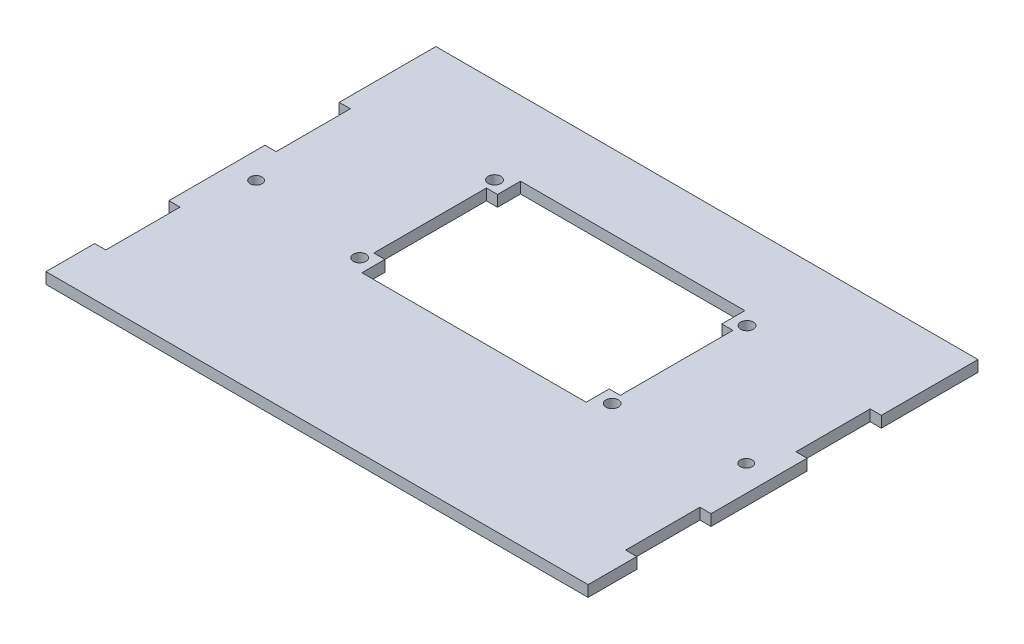
SolidWorks part; units mm, degrees
ref_plane "Front Plane" through (0, 0, 0) normal (0, 0, 1) x (1, 0, 0)
ref_plane "Top Plane" through (0, 0, 0) normal (0, 1, 0) x (1, 0, 0)
ref_plane "Right Plane" through (0, 0, 0) normal (1, 0, 0) x (0, 0, -1)
other "Configuration Table"
sketch "Sketch1" plane through (0, 0, 0) normal (0, 1, 0) x (1, 0, 0)
  line L1 (73, -52.5) -> (-73, -52.5)
  line L2 (73, -52.5) -> (73, 52.5)
  line L3 (73, 52.5) -> (-73, 52.5)
  line L4 (-73, -52.5) -> (-73, 52.5)
  line L5 (73, -52.5) -> (-73, 52.5) construction
  line L6 (73, 52.5) -> (-73, -52.5) construction
  point P0 (0, 0)
  dimension "D1" = 146
  dimension "D2" = 105
extrude "Boss-Extrude1" add sketch "Sketch1" along normal blind 3
sketch "Sketch2" plane through (0, 3, 0) normal (0, 1, 0) x (1, 0, 0)
  line L9 (73, -52.5) -> (73, 52.5) construction
  line L14 (-70, 26.47) -> (-70, 6.47)
  line L42 (-70, 26.47) -> (-73, 26.47)
  line L43 (-73, 52.5) -> (-73, -52.5) construction
  line L44 (-73, 26.47) -> (-73, 6.47)
  line L45 (-73, 6.47) -> (-70, 6.47)
  line L46 (70, 6.47) -> (70, 26.47)
  line L47 (70, 26.47) -> (73, 26.47)
  line L48 (73, 26.47) -> (73, 6.47)
  line L49 (73, 6.47) -> (70, 6.47)
  line L54 (-70, -39.4) -> (-70, -19.4)
  line L55 (-70, -19.4) -> (-73, -19.4)
  line L56 (-73, -19.4) -> (-73, -39.4)
  line L57 (-73, -39.4) -> (-70, -39.4)
  line L67 (70, -39.4) -> (70, -19.4)
  line L68 (70, -19.4) -> (73, -19.4)
  line L69 (73, -19.4) -> (73, -39.4)
  line L70 (73, -39.4) -> (70, -39.4)
  dimension "D2" = 13.1
  dimension "D9" = 20
  dimension "D11" = 3
  dimension "D12" = 25.87
  dimension "D13" = 20
extrude "Cut-Extrude1" cut sketch "Sketch2" against normal blind 10
sketch "Sketch3" plane through (0, 0, 0) normal (0, -1, 0) x (-1, 0, 0)
  line L0 (0, 52.5) -> (0, -52.5) construction
  line L1 (-34, 29.3) -> (-34, 32.5) construction
  line L2 (34, 29.3) -> (34, 32.5) construction
  line L3 (-73, 52.5) -> (73, 52.5) construction
  line L4 (73, -52.5) -> (-73, -52.5) construction
  line L6 (-37.2, 32.5) -> (-37.2, -10.22) construction
  line L7 (-37.2, -10.22) -> (37.2, -10.22) construction
  line L8 (37.2, -10.22) -> (37.2, 32.5) construction
  line L9 (37.2, 32.5) -> (-37.2, 32.5) construction
  line L10 (-37.2, -7.02) -> (-34, -7.02) construction
  line L11 (-37.2, 29.3) -> (-34, 29.3) construction
  line L12 (37.2, 29.3) -> (34, 29.3) construction
  line L13 (37.2, -7.02) -> (34, -7.02) construction
  line L14 (-34, -7.02) -> (-34, -10.22) construction
  line L15 (34, -7.02) -> (34, -10.22) construction
  line L16 (-30.2, 32.5) -> (-30.2, -10.22)
  line L17 (-30.2, -10.22) -> (30.2, -10.22)
  line L18 (30.2, -10.22) -> (30.2, 32.5)
  line L19 (30.2, 32.5) -> (-30.2, 32.5)
  line L20 (-30.2, 32.5) -> (30.2, -10.22) construction
  line L21 (30.2, 32.5) -> (-30.2, -10.22) construction
  circle A0 centre (-34, 29.3) radius 1.7
  circle A1 centre (-34, -7.02) radius 1.7
  circle A2 centre (34, 29.3) radius 1.7
  circle A3 centre (34, -7.02) radius 1.7
  point P6 (0, 0)
  point P29 (0, 11.14)
  dimension "D4" = 36.32
  dimension "D6" = 7
  dimension "D7" = 20
  dimension "D1" = 42.72
  dimension "D2" = 74.4
  dimension "D3" = 68
  dimension "D5" = 7
extrude "Cut-Extrude2" cut sketch "Sketch3" against normal blind 3
sketch "Sketch5" plane through (0, 0, 0) normal (0, -1, 0) x (-1, 0, 0)
  line L0 (30.2, -4.02) -> (33.2, -4.02)
  line L1 (30.2, -10.22) -> (30.2, 32.5) construction
  line L2 (33.2, -4.02) -> (33.2, 26.3)
  line L3 (33.2, 26.3) -> (30.2, 26.3)
  line L4 (30.2, 26.3) -> (30.2, -4.02)
  line L5 (-30.2, -4.02) -> (-33.2, -4.02)
  line L6 (-30.2, 32.5) -> (-30.2, -10.22) construction
  line L7 (-33.2, -4.02) -> (-33.2, 26.3)
  line L8 (-33.2, 26.3) -> (-30.2, 26.3)
  line L9 (-30.2, 26.3) -> (-30.2, -4.02)
  circle A0 centre (34, -7.02) radius 1.7 construction
  circle A1 centre (34, 29.3) radius 1.7 construction
  point P8 (31.7, -4.02)
  dimension "D1" = 3
  dimension "D2" = 3
  dimension "D3" = 3
  dimension "D4" = 3
extrude "Cut-Extrude4" cut sketch "Sketch5" against normal through all
sketch "Sketch6" plane through (0, 0, 0) normal (0, -1, 0) x (1, 0, 0)
  line L0 (-73, 52.5) -> (73, 52.5) construction
  line L1 (73, 19.4) -> (73, -6.47) construction
  circle A0 centre (-66, 2.92) radius 1.6
  circle A1 centre (66, 2.92) radius 1.6
  dimension "D2" = 7
  dimension "D1" = 49.58
  dimension "D3" = 7
extrude "Cut-Extrude5" cut sketch "Sketch6" against normal blind 10
